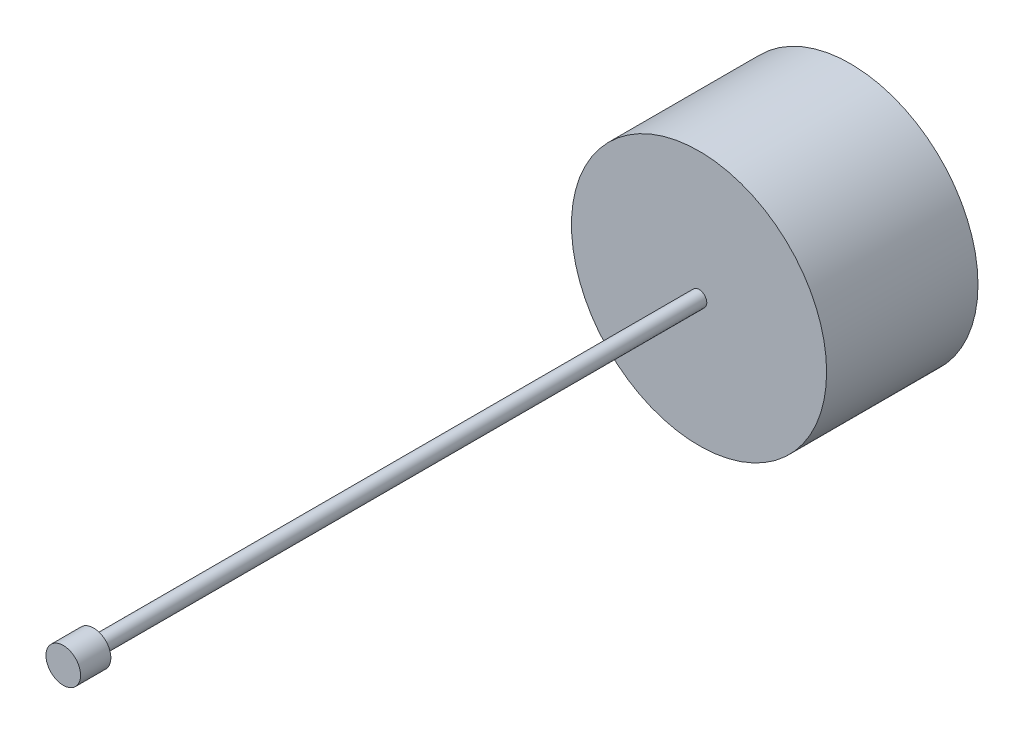
SolidWorks part; units mm, degrees
material "915 Antenna Placeholder"
ref_plane "Front Plane" through (0, 0, 0) normal (0, 0, 1) x (1, 0, 0)
ref_plane "Top Plane" through (0, 0, 0) normal (0, 1, 0) x (1, 0, 0)
ref_plane "Right Plane" through (0, 0, 0) normal (1, 0, 0) x (0, 0, -1)
sketch "Sketch1" plane through (0, 0, 0) normal (0, 0, 1) x (1, 0, 0)
  circle A0 centre (0, 0) radius 29.5
  dimension "D1" = 59
extrude "Boss-Extrude1" add sketch "Sketch1" along normal blind 35 contours A0
sketch "Sketch2" plane through (0, 0, 35) normal (0, 0, 1) x (1, 0, 0)
  circle A0 centre (0, 0) radius 1.7907
  dimension "D1" = 3.5814
extrude "Boss-Extrude2" add sketch "Sketch2" along normal blind 140
sketch "Sketch3" plane through (0, 0, 175) normal (0, 0, 1) x (1, 0, 0)
  circle A0 centre (0, 0) radius 4
  dimension "D1" = 8
extrude "Boss-Extrude3" add sketch "Sketch3" along normal blind 7
